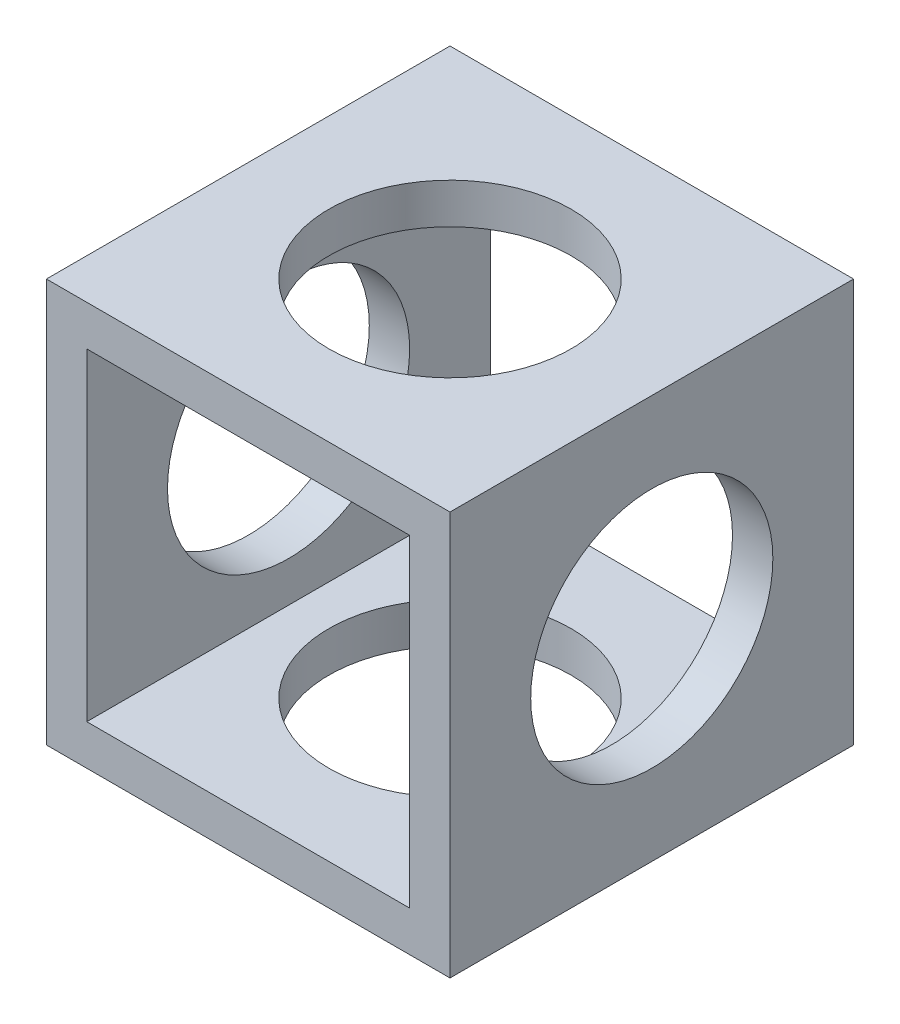
SolidWorks part; units mm, degrees
material "AISI 1020"
ref_plane "Alzado" through (0, 0, 0) normal (0, 0, 1) x (1, 0, 0)
ref_plane "Planta" through (0, 0, 0) normal (0, 1, 0) x (1, 0, 0)
ref_plane "Vista lateral" through (0, 0, 0) normal (1, 0, 0) x (0, 0, -1)
sketch "Croquis1" plane through (0, 0, 0) normal (0, 0, 1) x (1, 0, 0)
  line L1 (-25, -25) -> (25, -25)
  line L2 (-25, -25) -> (-25, 25)
  line L3 (-25, 25) -> (25, 25)
  line L4 (25, -25) -> (25, 25)
  line L5 (-25, -25) -> (25, 25) construction
  line L6 (-25, 25) -> (25, -25) construction
  line L7 (-20, -20) -> (20, -20)
  line L8 (-20, -20) -> (-20, 20)
  line L9 (-20, 20) -> (20, 20)
  line L10 (20, -20) -> (20, 20)
  line L11 (-20, -20) -> (20, 20) construction
  line L12 (-20, 20) -> (20, -20) construction
  point P0 (0, 0)
  point P6 (0, 0)
  dimension "D1" = 50
  dimension "D2" = 50
  dimension "D3" = 5
extrude "Saliente-Extruir1" add sketch "Croquis1" against normal blind 50
sketch "Croquis2" plane through (25, 0, 0) normal (1, 0, 0) x (0, 0, -1)
  circle A0 centre (25, 0) radius 15
  dimension "D1" = 30
  dimension "D2" = 25
extrude "Cortar-Extruir1" cut sketch "Croquis2" against normal through all
sketch "Croquis3" plane through (0, 25, 0) normal (0, 1, 0) x (1, 0, 0)
  circle A0 centre (0, 25) radius 15
  dimension "D2" = 30
  dimension "D1" = 25
extrude "Cortar-Extruir2" cut sketch "Croquis3" against normal through all
